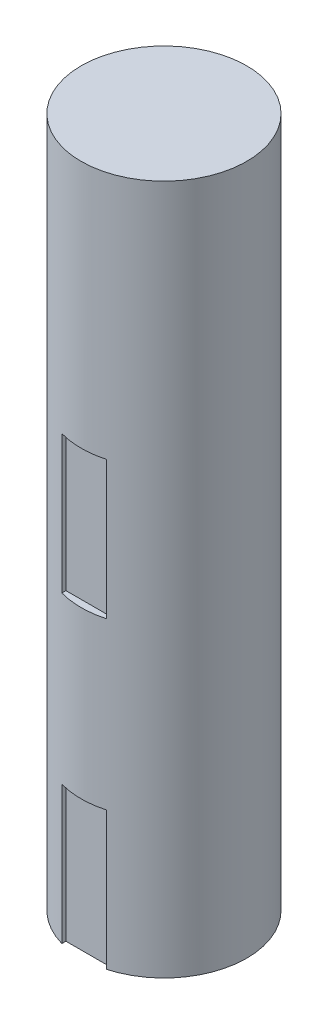
SolidWorks part; units mm, degrees
ref_plane "Front Plane" through (0, 0, 0) normal (0, 0, 1) x (1, 0, 0)
ref_plane "Top Plane" through (0, 0, 0) normal (0, 1, 0) x (1, 0, 0)
ref_plane "Right Plane" through (0, 0, 0) normal (1, 0, 0) x (0, 0, -1)
sketch "Sketch2" plane through (0, 0, 0) normal (0, 1, 0) x (1, 0, 0)
  circle A0 centre (0, 0) radius 30
  dimension "D1" = 60
extrude "Boss-Extrude1" add sketch "Sketch2" along normal mid plane 250
sketch "Sketch3" plane through (0, -125, 0) normal (0, -1, 0) x (1, 0, 0)
  line L0 (0, 0) -> (0, 30.92) construction
  line L1 (-10.394, 0) -> (-10.394, 36.9287)
  line L2 (8.0953, 27.42) -> (-8.0953, 27.42)
  line L3 (8.0953, 27.42) -> (8.0953, 34.42)
  line L4 (8.0953, 34.42) -> (-8.0953, 34.42)
  line L5 (-8.0953, 27.42) -> (-8.0953, 34.42)
  line L6 (8.0953, 27.42) -> (-8.0953, 34.42) construction
  line L7 (8.0953, 34.42) -> (-8.0953, 27.42) construction
  line L8 (10.394, 0) -> (10.394, 36.9287)
  circle M4 centre (0, 0) radius 30
  dimension "D1" = 30.92
  dimension "D2" = 7
extrude "Cut-Extrude1" cut sketch "Sketch3" against normal blind 50 contours L5 L3 L4 M4 | L5 L2 L3 M4
ref_plane "Plane1" through (0, -15, 0) normal (0, -1, 0) x (-1, 0, 0)
sketch "Sketch4" plane through (0, -15, 0) normal (0, -1, 0) x (-1, 0, 0)
  line L3 (8.0953, -28.8871) -> (8.0953, -27.42)
  line L4 (8.0953, -27.42) -> (-8.0953, -27.42)
  line L5 (-8.0953, -27.42) -> (-8.0953, -28.8871)
  line L6 (8.0953, -28.8871) -> (8.0953, -27.42)
  line L7 (8.0953, -27.42) -> (-8.0953, -27.42)
  line L8 (-8.0953, -27.42) -> (-8.0953, -28.8871)
  arc A1 (-8.0953, -28.8871) -> (8.0953, -28.8871) centre (0, 0) ccw
  arc A2 (-8.0953, -28.8871) -> (8.0953, -28.8871) centre (0, 0) ccw
  dimension "D1" = 0
extrude "Cut-Extrude2" cut sketch "Sketch4" against normal blind 50
